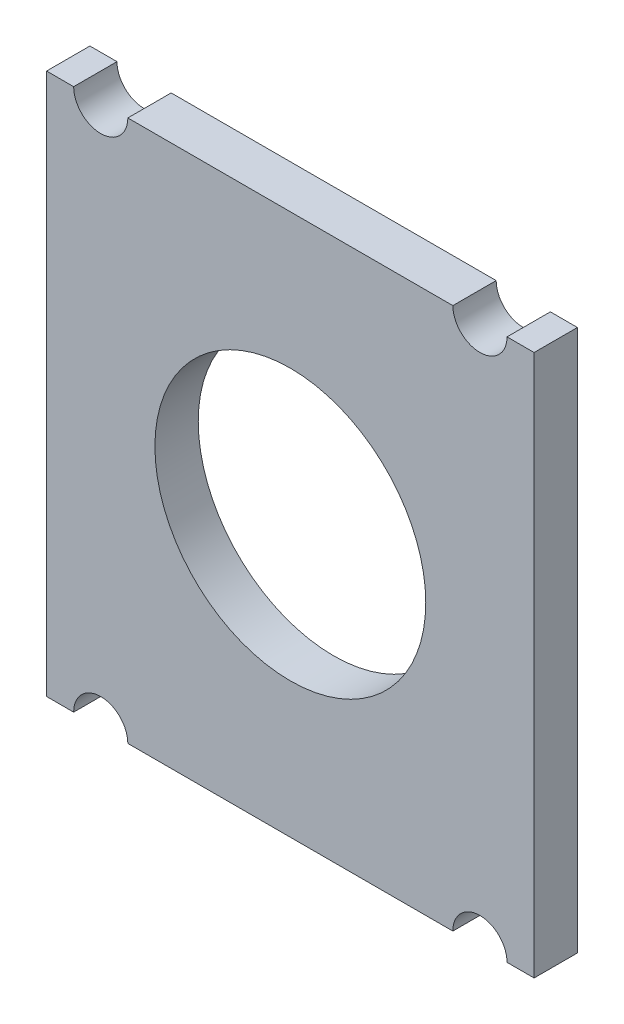
SolidWorks part; units mm, degrees
ref_plane "Front Plane" through (0, 0, 0) normal (0, 0, 1) x (1, 0, 0)
ref_plane "Top Plane" through (0, 0, 0) normal (0, 1, 0) x (1, 0, 0)
ref_plane "Right Plane" through (0, 0, 0) normal (1, 0, 0) x (0, 0, -1)
sketch "Sketch1" plane through (0, 0, 0) normal (0, 0, 1) x (1, 0, 0)
  line L0 (9.5, 0) -> (0.5, 0)
  line L1 (0.5, 0) -> (0.5, 10)
  line L2 (0.5, 10) -> (9.5, 10)
  line L3 (9.5, 10) -> (9.5, 0)
extrude "BOARD" add sketch "Sketch1" along normal blind 0.8 separate body
sketch "Sketch2" plane through (0, 0, 0) normal (0, 0, 1) x (1, 0, 0)
  circle A0 centre (5, 5) radius 2.5
extrude "NON-PLATED HOLES" cut sketch "Sketch2" along normal through all
sketch "Sketch3" plane through (0, 0, 0) normal (0, 0, 1) x (1, 0, 0)
  circle A0 centre (1.5, 0) radius 0.5
  circle A1 centre (1.5, 10) radius 0.5
  circle A2 centre (8.5, 10) radius 0.5
  circle A3 centre (8.5, 0) radius 0.5
extrude "PLATED HOLES" cut sketch "Sketch3" along normal through all
ref_plane "Plane1" through (0, 0, 100) normal (0, 0, 1) x (1, 0, 0)
